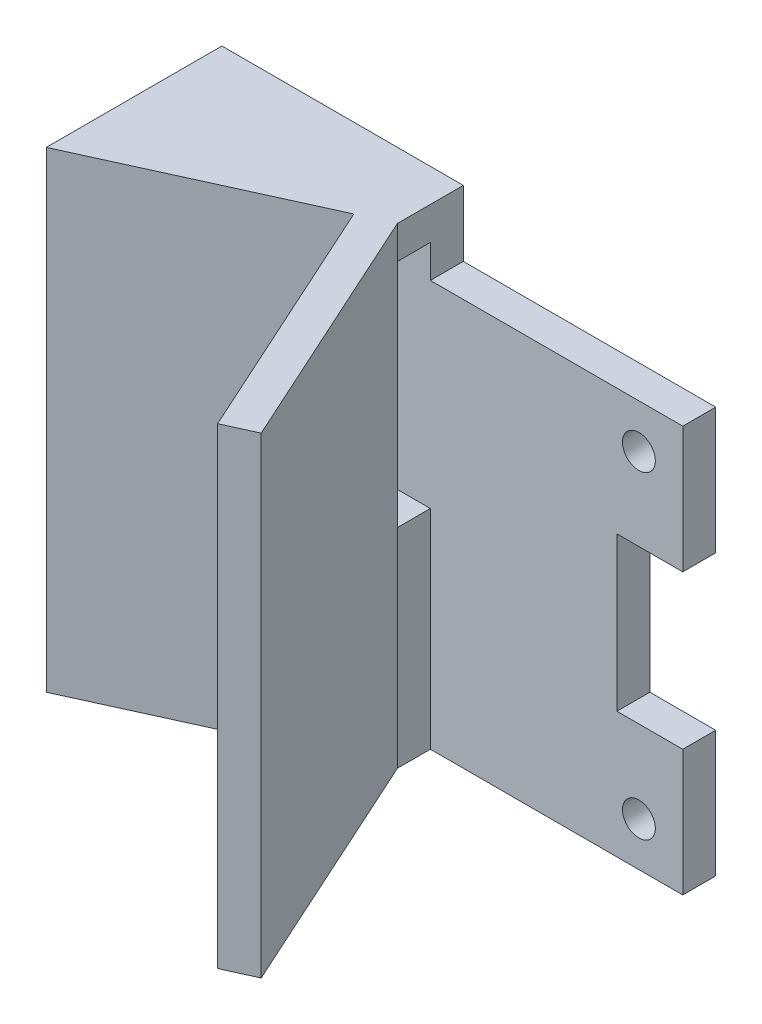
SolidWorks part; units mm, degrees
ref_plane "Alzado" through (0, 0, 0) normal (0, 0, 1) x (1, 0, 0)
ref_plane "Planta" through (0, 0, 0) normal (0, 1, 0) x (1, 0, 0)
ref_plane "Vista lateral" through (0, 0, 0) normal (1, 0, 0) x (0, 0, -1)
sketch "Croquis1" plane through (0, 0, 0) normal (0, 0, 1) x (1, 0, 0)
  line L1 (-52.1973, 33.4619) -> (-4.1973, 33.4619)
  line L2 (-56.1973, 29.4619) -> (-56.1973, 0.4619)
  line L3 (-52.4067, -3.5381) -> (-4.1973, -3.5381)
  line L4 (-4.1973, 33.4619) -> (-4.1973, -3.5381)
  line L5 (-56.1973, 24.9619) -> (-49.1973, 24.9619)
  line L6 (-56.1973, 24.9619) -> (-56.1973, 4.9619)
  line L7 (-56.1973, 4.9619) -> (-49.1973, 4.9619)
  line L8 (-49.1973, 24.9619) -> (-49.1973, 4.9619)
  line L9 (-4.1973, 21.9619) -> (-10.1973, 21.9619)
  line L10 (-4.1973, 21.9619) -> (-4.1973, 7.9619)
  line L11 (-4.1973, 7.9619) -> (-10.1973, 7.9619)
  line L12 (-10.1973, 21.9619) -> (-10.1973, 7.9619)
  circle A0 centre (-52.1973, 29.4619) radius 1.5
  circle A1 centre (-8.1973, 29.4619) radius 1.5
  circle A2 centre (-52.1915, 0.4619) radius 1.5
  circle A3 centre (-8.1973, 0.4619) radius 1.5
  arc A4 (-56.1973, 29.4619) -> (-52.1973, 33.4619) centre (-52.1973, 29.4619) cw
  arc A5 (-52.4067, -3.5381) -> (-56.1973, 0.4619) centre (-52.1915, 0.4619) cw
  dimension "D3" = 4
  dimension "D5" = 44
  dimension "D6" = 4
  dimension "D7" = 29
  dimension "D1" = 8.5
  dimension "D2" = 20
  dimension "D4" = 4
  dimension "D8" = 4
  dimension "D9" = 4
  dimension "D10" = 7
  dimension "D11" = 11.5
  dimension "D12" = 6
  dimension "D13" = 14
  dimension "D14" = 48
extrude "Saliente-Extruir1" add sketch "Croquis1" along normal blind 3 contours A5 L3 L4 L11 L12 L9 L1 A4 L2 L5 L8 L7 A3 A2 A1 A0
sketch "Croquis3" plane through (0, 0, 3) normal (0, 0, 1) x (1, 0, 0)
  line L0 (-52.1973, 33.4619) -> (-4.1973, 33.4619) construction
  line L1 (-49.1973, 33.4619) -> (-27.1973, 33.4619)
  line L2 (-49.1973, 33.4619) -> (-49.1973, -3.5381)
  line L3 (-49.1973, -3.5381) -> (-27.1973, -3.5381)
  line L4 (-27.1973, 33.4619) -> (-27.1973, -3.5381)
  line L5 (-52.4067, -3.5381) -> (-4.1973, -3.5381) construction
  circle A0 centre (-52.1973, 29.4619) radius 1.5 construction
  dimension "D1" = 3
  dimension "D2" = 22
extrude "Saliente-Extruir2" add sketch "Croquis3" along normal blind 13
sketch "Croquis4" plane through (0, -3.5381, 0) normal (0, -1, 0) x (1, 0, 0)
  line L0 (-27.1973, 16) -> (-27.1973, 6.0021)
  line L1 (-27.1973, 16) -> (-27.1973, 3) construction
  line L2 (-27.1973, 16) -> (-49.1973, 16)
  line L7 (-27.1973, 6.0021) -> (-49.1973, 16)
  line L8 (-27.1973, 3) -> (-4.1973, 3) construction
  dimension "D1" = 3.0021
extrude "Cortar-Extruir1" cut sketch "Croquis4" against normal up to vertex
sketch "Croquis6" plane through (0, 33.4619, 0) normal (0, 1, 0) x (1, 0, 0)
  line L0 (-27.1973, -6.0021) -> (-49.1973, -16)
  line L1 (-49.1973, -16) -> (-49.1973, 0)
  line L2 (-52.1973, 0) -> (-4.1973, 0) construction
  line L3 (-49.1973, 0) -> (-27.1973, 0)
  line L4 (-27.1973, 0) -> (-27.1973, -6.0021)
extrude "Saliente-Extruir4" add sketch "Croquis6" along normal blind 6
sketch "Croquis7" plane through (-27.1973, 0, 0) normal (1, 0, 0) x (0, 0, -1)
  line L0 (-6.0021, 39.4619) -> (-6.0021, -3.5381) construction
  line L1 (-6.0021, 15.4619) -> (-3, 15.4619)
  line L2 (-6.0021, 15.4619) -> (-6.0021, 36.4619)
  line L3 (-6.0021, 36.4619) -> (-3, 36.4619)
  line L4 (-3, 15.4619) -> (-3, 36.4619)
  line L5 (-6.0021, -3.5381) -> (-3, -3.5381) construction
  line L6 (-6.0021, 39.4619) -> (0, 39.4619) construction
  dimension "D1" = 19
  dimension "D2" = 3
extrude "Cortar-Extruir2" cut sketch "Croquis7" against normal up to vertex (22 mm away) up to point (-49.1973, 39.4619, 0)
sketch "Croquis8" plane through (-2.3947, 0, -5.2695) normal (0.4137, 0, 0.9104) x (0.9104, 0, -0.4137)
  line L0 (-51.4089, 39.4619) -> (-27.2436, 39.4619) construction
  line L1 (-27.2436, -3.5381) -> (-30.2436, -3.5381)
  line L2 (-27.2436, -3.5381) -> (-27.2436, 39.4619)
  line L3 (-27.2436, 39.4619) -> (-30.2436, 39.4619)
  line L4 (-30.2436, -3.5381) -> (-30.2436, 39.4619)
  dimension "D1" = 3
extrude "Saliente-Extruir5" add sketch "Croquis8" along normal blind 25
